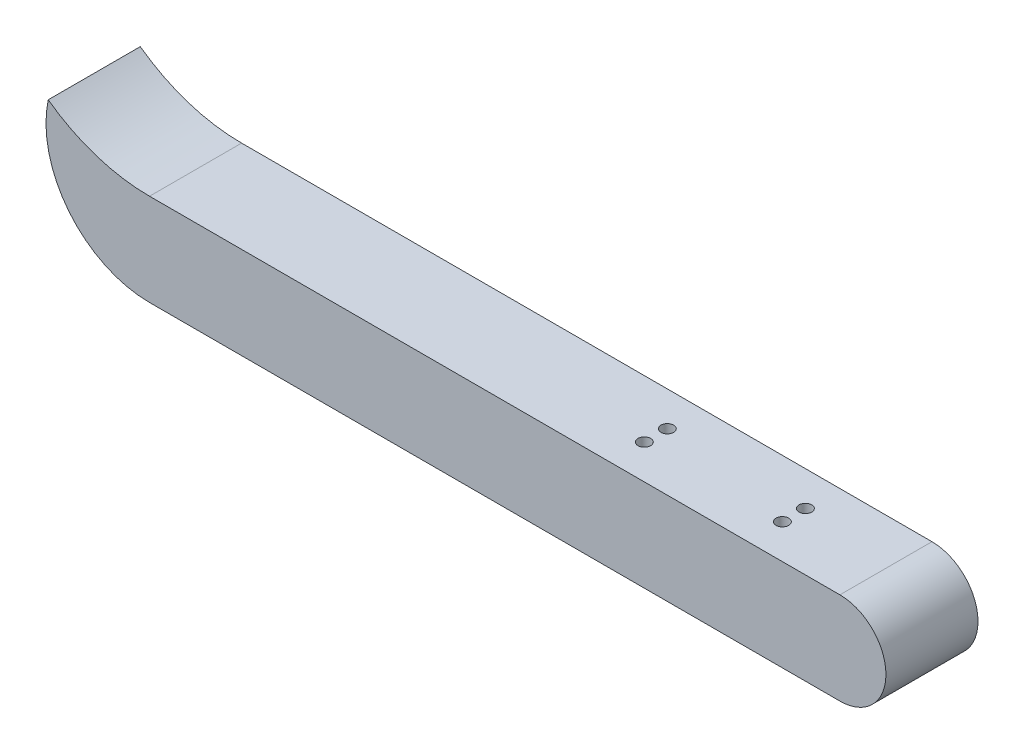
SolidWorks part; units mm, degrees
other "Markup1"
sketch "Sketch5" plane through (-60, 110, 130) normal (-0.0294, 0.1713, 0.9848) x (0.9994, -0.0137, 0.0322)
other "Markup2"
sketch "Sketch6" plane through (-60, 90, 130) normal (-0.0446, 0.48, 0.8761) x (0.9986, 0.0449, 0.0262)
material "Beech"
ref_plane "Front Plane" through (0, 0, 0) normal (0, 0, 1) x (1, 0, 0)
ref_plane "Top Plane" through (0, 0, 0) normal (0, 1, 0) x (1, 0, 0)
ref_plane "Right Plane" through (0, 0, 0) normal (1, 0, 0) x (0, 0, -1)
sketch "Sketch1" plane through (0, 0, 0) normal (0, 0, 1) x (1, 0, 0)
  line L0 (0, 0) -> (300, 0)
  line L14 (0, 40) -> (300, 40)
  arc A9 (0, 0) -> (-44.0315, 54.2857) centre (0, 45) cw
  arc A10 (0, 40) -> (-44.0315, 54.2857) centre (0, 115) cw
  arc A11 (300, 40) -> (300, 0) centre (300, 20) cw
  dimension "D4" = 14.2857
  dimension "D7" = 75
  dimension "D8" = 45
  dimension "D2" = 20
  dimension "D1" = 300
  dimension "D3" = 54.2857
extrude "Boss-Extrude1" add sketch "Sketch1" along normal blind 40
hole_wizard "CBORE for M5 Hex Head Bolt3" positions "Sketch14" profile "Sketch15" counterbore size "M5" standard "ANSI Metric" end condition through all
sketch "Sketch14" plane through (0, 0, 0) normal (0, -1, 0) x (-1, 0, 0)
  line L0 (-300, -40) -> (-300, 0) construction
  line L1 (0, -40) -> (-300, -40) construction
  line L2 (0, 0) -> (-300, 0) construction
  point P0 (-260, -15)
  point P2 (-260, -25)
  point P4 (-200, -25)
  point P6 (-200, -15)
  dimension "D1" = 40
  dimension "D2" = 40
  dimension "D3" = 60
  dimension "D4" = 60
  dimension "D5" = 25
  dimension "D6" = 25
  dimension "D7" = 25
  dimension "D8" = 25
sketch "Sketch15" plane through (260, 0, 15) normal (1, 0, 0) x (0, 0, -1)
  line L0 (0, 0) -> (0, 54.2857)
  line L1 (0, 54.2857) -> (2.75, 54.2857)
  line L3 (2.75, 54.2857) -> (2.75, 3.58)
  line L4 (2.75, 3.58) -> (6.12, 3.58)
  line L5 (6.12, 3.58) -> (6.12, 0)
  line L7 (6.12, 0) -> (0, 0)
  line L11 (0, -6.35) -> (0, 107.95) construction
  dimension "Thru Hole Dia." = 5.5
  dimension "Thru Hole Depth" = 54.2857
  dimension "C'Bore Dia." = 12.24
  dimension "C'Bore Depth" = 3.58
